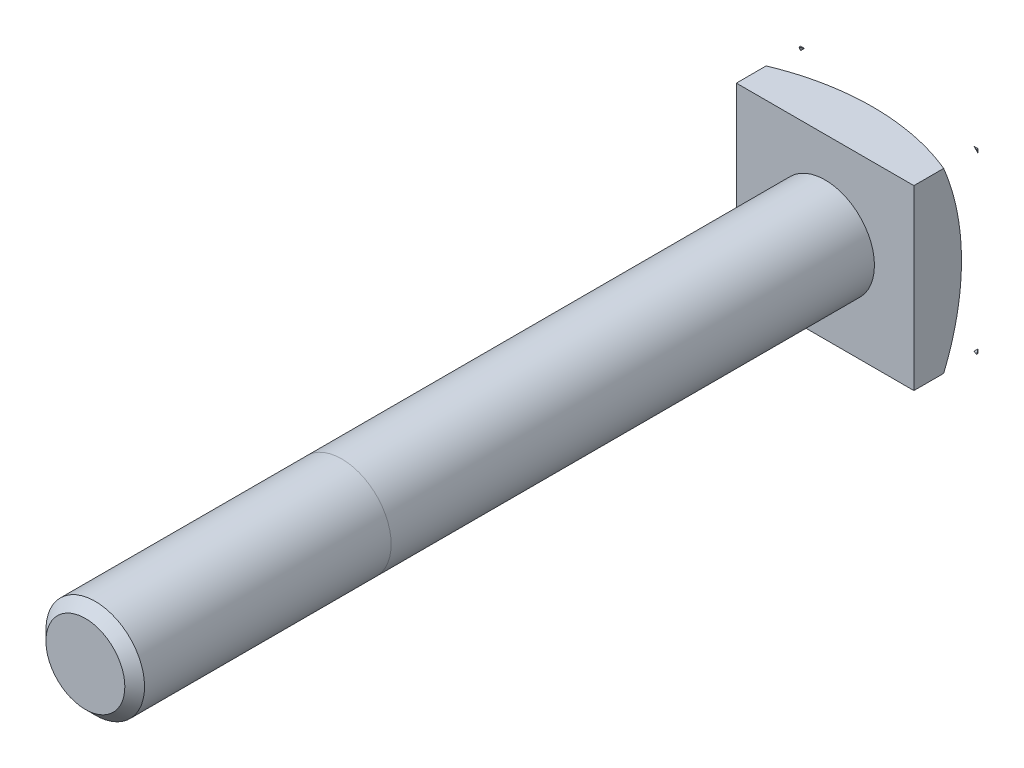
SolidWorks part; units mm, degrees
ref_plane "Front Plane" through (0, 0, 0) normal (0, 0, 1) x (1, 0, 0)
ref_plane "Top Plane" through (0, 0, 0) normal (0, 1, 0) x (1, 0, 0)
ref_plane "Right Plane" through (0, 0, 0) normal (1, 0, 0) x (0, 0, -1)
sketch "Sketch1" plane through (0, 0, 0) normal (0, 0, 1) x (1, 0, 0)
  line L1 (-9, 9) -> (9, 9)
  line L2 (-9, 9) -> (-9, -9)
  line L3 (-9, -9) -> (9, -9)
  line L4 (9, 9) -> (9, -9)
  line L5 (-9, 9) -> (9, -9) construction
  line L6 (-9, -9) -> (9, 9) construction
  point P0 (0, 0)
extrude "Boss-Extrude1" add sketch "Sketch1" along normal mid plane 6.5
sketch "Sketch2" plane through (0, 0, 3.25) normal (0, 0, 1) x (1, 0, 0)
  circle A0 centre (0, 0) radius 5
extrude "Boss-Extrude3" add sketch "Sketch2" along normal blind 75
sketch "Sketch3" plane through (0, 0, 0) normal (0, 1, 0) x (1, 0, 0)
  line L0 (0, -21.75) -> (0, 6.1727) construction
  line L2 (0, -21.75) -> (27.9227, -21.75) construction
  line L3 (0, 3.25) -> (0, 6.1727)
  line L4 (25, -21.75) -> (27.9227, -21.75)
  arc A0 (25, -21.75) -> (0, 3.25) centre (0, -21.75) ccw
  arc A1 (27.9227, -21.75) -> (0, 6.1727) centre (0, -21.75) ccw
revolve "Cut-Revolve1" cut sketch "Sketch3" angle 360 about L0
sketch "Sketch4" plane through (0, 0, 0) normal (0, 1, 0) x (1, 0, 0)
  line L0 (-5, -52.25) -> (5, -52.25)
  line L1 (-5, -3.25) -> (-5, -78.25) construction
  line L2 (5, -78.25) -> (5, -3.25) construction
  line L3 (-5, -78.25) -> (5, -78.25) construction
  dimension "D1" = 26
split line "Split Line1"
chamfer "Chamfer1" distance 1 angle 45 1 edges at (5, 0, 78.25)
